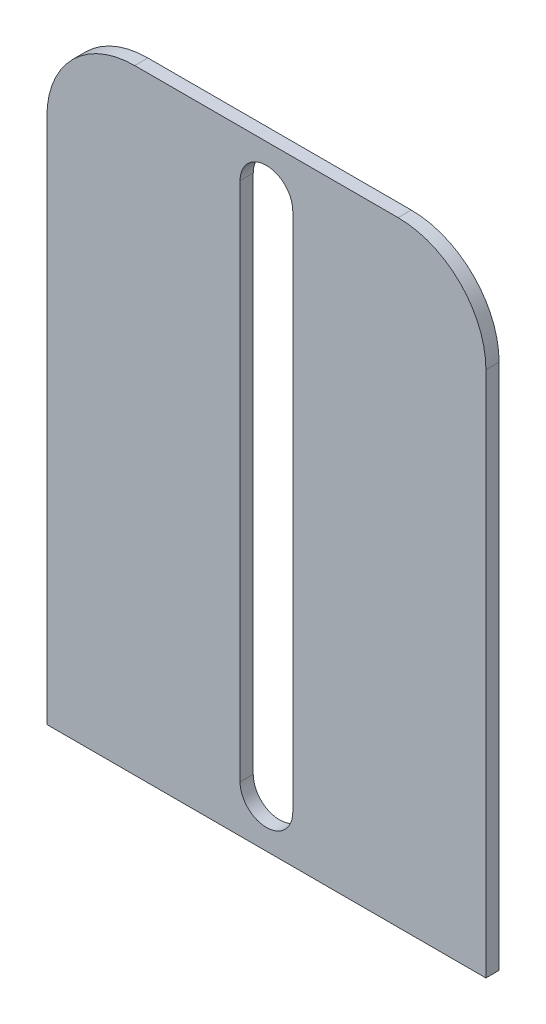
SolidWorks part; units mm, degrees
ref_plane "Front Plane" through (0, 0, 0) normal (0, 0, 1) x (1, 0, 0)
ref_plane "Top Plane" through (0, 0, 0) normal (0, 1, 0) x (1, 0, 0)
ref_plane "Right Plane" through (0, 0, 0) normal (1, 0, 0) x (0, 0, -1)
sketch "Sketch1" plane through (0, 0, 0) normal (0, 0, 1) x (1, 0, 0)
  line L0 (0, -29.6533) -> (0, 29.6533) construction
  line L1 (-25, -35) -> (25, -35)
  line L2 (-25, -35) -> (-25, 35)
  line L3 (-25, 35) -> (25, 35)
  line L4 (25, -35) -> (25, 35)
  line L5 (-25, -35) -> (25, 35) construction
  line L6 (-25, 35) -> (25, -35) construction
  line L7 (-3, -29.6533) -> (-3, 29.6533)
  line L8 (3, -29.6533) -> (3, 29.6533)
  arc A0 (-3, -29.6533) -> (3, -29.6533) centre (0, -29.6533) ccw
  arc A1 (3, 29.6533) -> (-3, 29.6533) centre (0, 29.6533) ccw
  point P0 (0, 0)
  point P8 (0, 0)
extrude "Boss-Extrude1" add sketch "Sketch1" along normal blind 1.5
fillet "Fillet1" radius 10 2 edges at (-25, 35, 0.75) (25, 35, 0.75)
